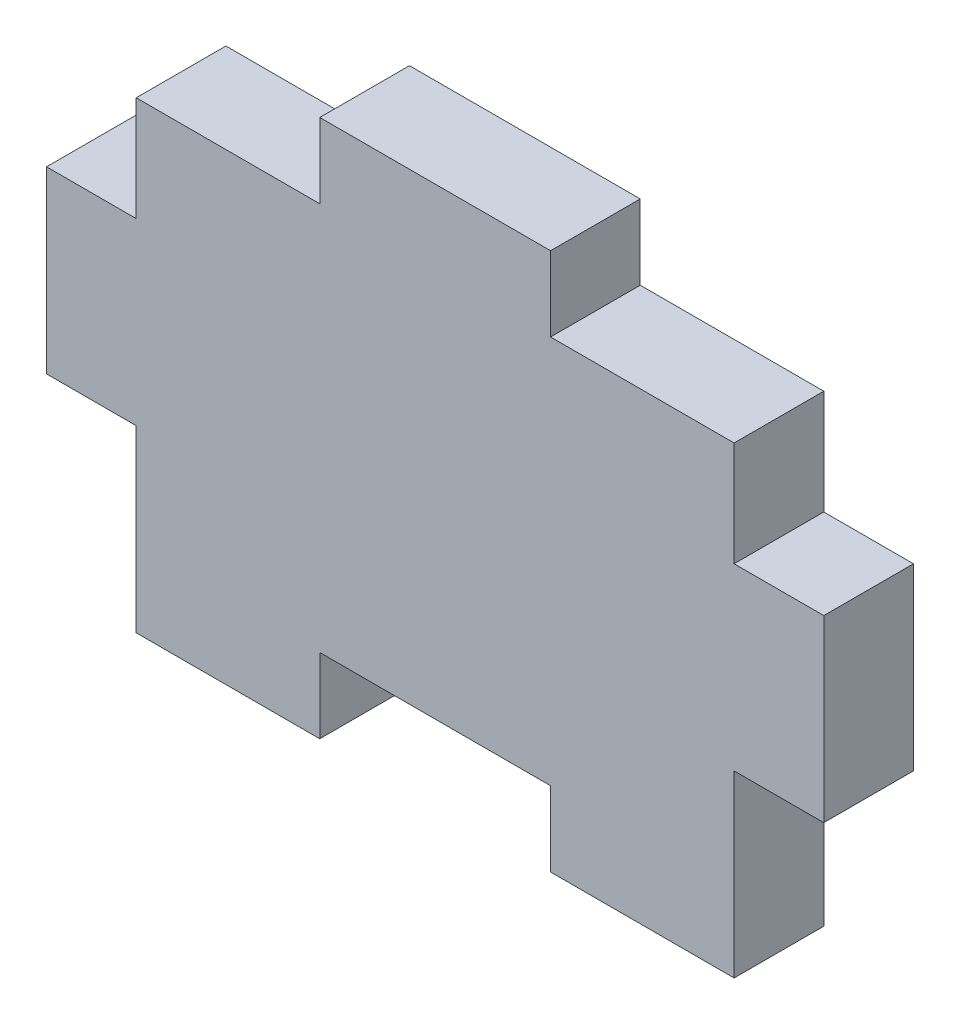
SolidWorks part; units mm, degrees
ref_plane "Front Plane" through (0, 0, 0) normal (0, 0, 1) x (1, 0, 0)
ref_plane "Top Plane" through (0, 0, 0) normal (0, 1, 0) x (1, 0, 0)
ref_plane "Right Plane" through (0, 0, 0) normal (1, 0, 0) x (0, 0, -1)
sketch "Sketch1" plane through (0, 0, 0) normal (0, 0, 1) x (1, 0, 0)
  line L0 (3.8602, -0.6189) -> (10, -0.6189)
  line L1 (10, -0.6189) -> (10, 5.3811)
  line L2 (10, 14.8811) -> (3.8602, 14.8811)
  line L3 (3.8602, -0.6189) -> (3.8602, 1.8811)
  line L4 (3.8602, 1.8811) -> (-3.8602, 1.8811)
  line L5 (3.8602, 14.8811) -> (3.8602, 17.3811)
  line L6 (3.8602, 17.3811) -> (-3.8602, 17.3811)
  line L7 (17.9979, 8.3811) -> (13, 8.3811) construction
  line L8 (13, 5.3811) -> (13, 11.3811)
  line L9 (13, 11.3811) -> (10, 11.3811)
  line L10 (13, 5.3811) -> (10, 5.3811)
  line L11 (10, 11.3811) -> (10, 14.8811)
  line L12 (0, 17.3811) -> (0, 1.8811) construction
  line L13 (-17.9979, 8.3811) -> (-13, 8.3811) construction
  line L14 (-10, 11.3811) -> (-10, 14.8811)
  line L15 (-13, 5.3811) -> (-10, 5.3811)
  line L16 (-13, 11.3811) -> (-10, 11.3811)
  line L17 (-13, 5.3811) -> (-13, 11.3811)
  line L18 (-3.8602, 14.8811) -> (-3.8602, 17.3811)
  line L19 (-3.8602, -0.6189) -> (-3.8602, 1.8811)
  line L20 (-10, 14.8811) -> (-3.8602, 14.8811)
  line L21 (-10, -0.6189) -> (-10, 5.3811)
  line L22 (-3.8602, -0.6189) -> (-10, -0.6189)
  dimension "D1" = 2.5
  dimension "D2" = 2.5
  dimension "D3" = 13
  dimension "D4" = 3
  dimension "D5" = 3
  dimension "D6" = 9
  dimension "D7" = 9
extrude "Boss-Extrude4" add sketch "Sketch1" along normal blind 3 contours L20 L18 L6 L5 L2 L11 L9 L8 L10 L1 L0 L3 L4 L19 L22 L21 L15 L17 L16 L14
